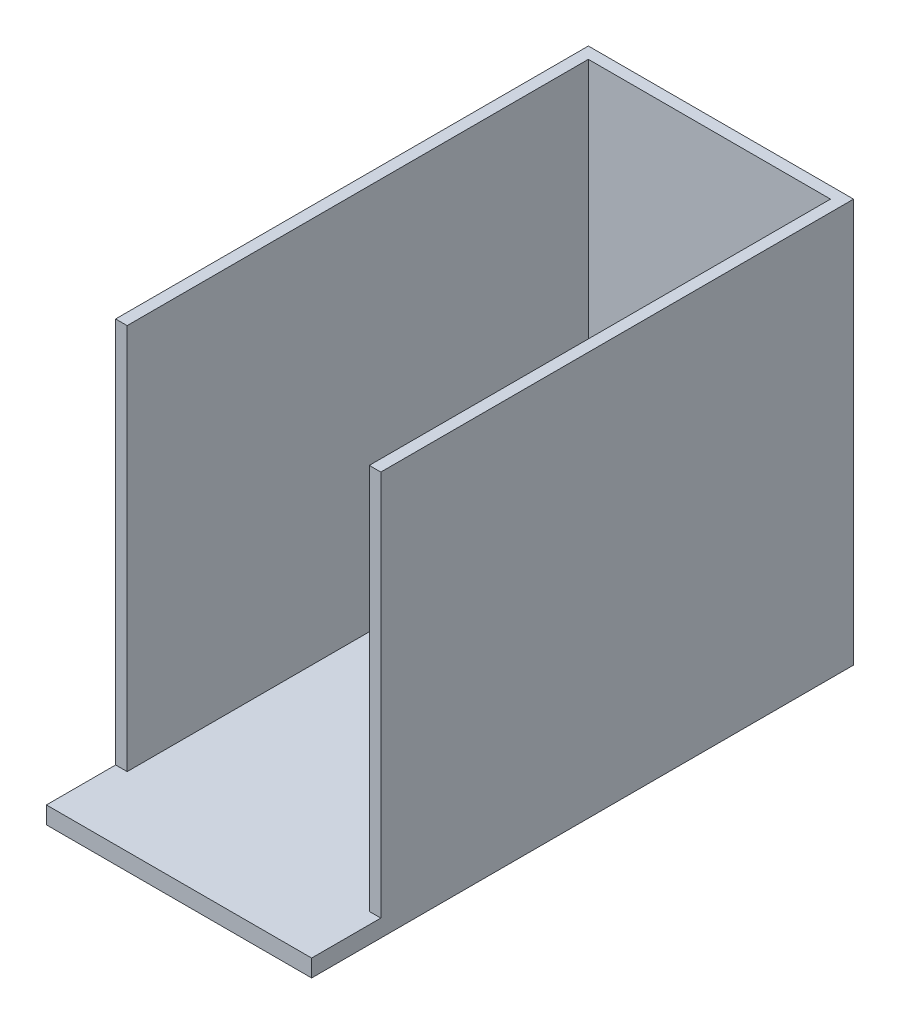
SolidWorks part; units mm, degrees
ref_plane "Front Plane" through (0, 0, 0) normal (0, 0, 1) x (1, 0, 0)
ref_plane "Top Plane" through (0, 0, 0) normal (0, 1, 0) x (1, 0, 0)
ref_plane "Right Plane" through (0, 0, 0) normal (1, 0, 0) x (0, 0, -1)
sketch "Sketch1" plane through (0, 0, 0) normal (0, 1, 0) x (1, 0, 0)
  line L1 (-146.05, -298.45) -> (146.05, -298.45)
  line L2 (-146.05, -298.45) -> (-146.05, 298.45)
  line L3 (-146.05, 298.45) -> (146.05, 298.45)
  line L4 (146.05, -298.45) -> (146.05, 298.45)
  line L5 (-146.05, -298.45) -> (146.05, 298.45) construction
  line L6 (-146.05, 298.45) -> (146.05, -298.45) construction
  point P0 (0, 0)
  dimension "D1" = 596.9
  dimension "D2" = 292.1
extrude "Boss-Extrude1" add sketch "Sketch1" along normal blind 19.05
sketch "Sketch2" plane through (0, 19.05, 0) normal (0, 1, 0) x (1, 0, 0)
  line L0 (-146.05, -222.25) -> (-146.05, 298.45)
  line L1 (-146.05, 298.45) -> (-146.05, -298.45) construction
  line L2 (-146.05, 298.45) -> (146.05, 298.45)
  line L3 (146.05, 298.45) -> (-146.05, 298.45) construction
  line L4 (146.05, -298.45) -> (146.05, 298.45) construction
  line L5 (146.05, 298.45) -> (146.05, -222.25)
  line L6 (146.05, -222.25) -> (133.35, -222.25)
  line L7 (133.35, -222.25) -> (133.35, 285.75)
  line L8 (133.35, 285.75) -> (-133.35, 285.75)
  line L9 (-133.35, 285.75) -> (-133.35, -222.25)
  line L10 (-133.35, -222.25) -> (-146.05, -222.25)
  point P5 (-94.8523, 311.15)
  point P16 (-114.6102, 275.6296)
  dimension "D1" = 76.2
  dimension "D2" = 12.7
  dimension "D3" = 12.7
extrude "Boss-Extrude2" add sketch "Sketch2" along normal blind 425.45
